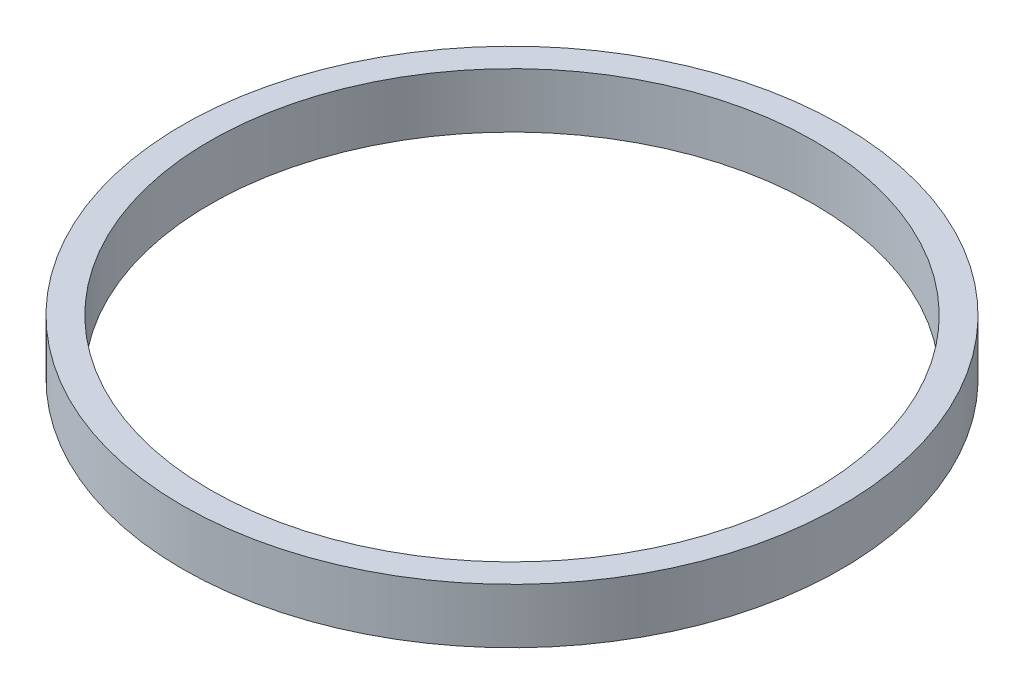
SolidWorks part; units mm, degrees
material "AISI 316 Annealed Stainless Steel Bar (SS)"
ref_plane "Front Plane" through (0, 0, 0) normal (0, 0, 1) x (1, 0, 0)
ref_plane "Top Plane" through (0, 0, 0) normal (0, 1, 0) x (1, 0, 0)
ref_plane "Right Plane" through (0, 0, 0) normal (1, 0, 0) x (0, 0, -1)
sketch "Sketch1" plane through (0, 0, 0) normal (0, 1, 0) x (1, 0, 0)
  circle A0 centre (0, 0) radius 11
  circle A1 centre (0, 0) radius 12
  dimension "D1" = 24
  dimension "D2" = 22
  dimension "D3" = 1
extrude "Boss-Extrude1" add sketch "Sketch1" along normal blind 2
